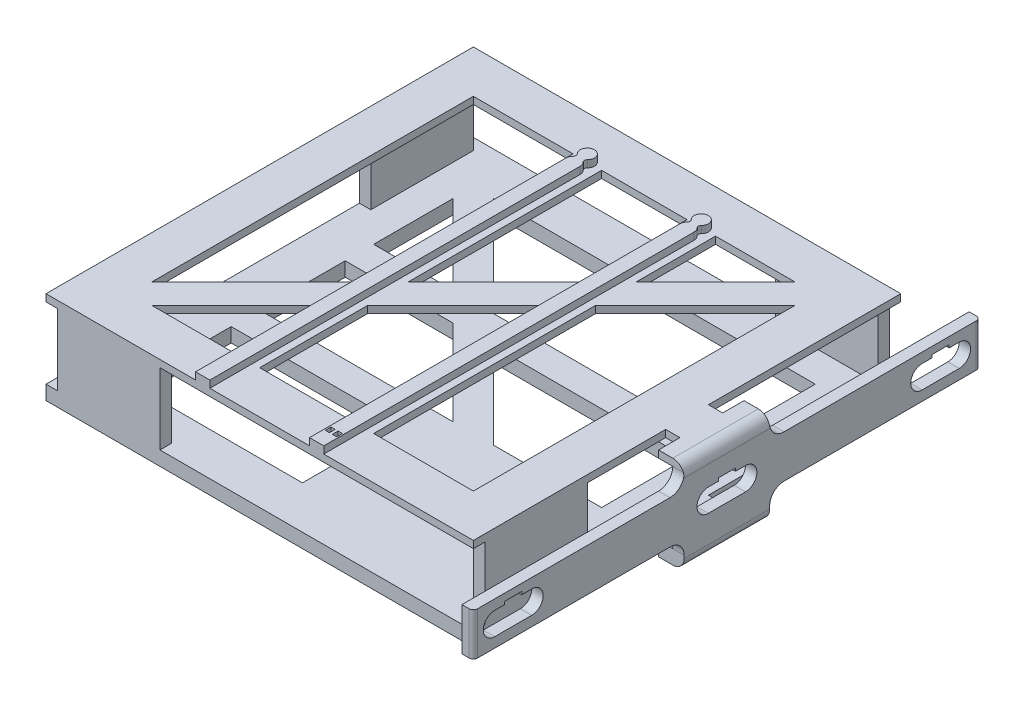
SolidWorks part; units mm, degrees
other "相机1"
material "3.0526 (EN-AW 3005)"
ref_plane "前视基准面" through (0, 0, 0) normal (0, 0, 1) x (1, 0, 0)
ref_plane "上视基准面" through (0, 0, 0) normal (0, 1, 0) x (1, 0, 0)
ref_plane "右视基准面" through (0, 0, 0) normal (1, 0, 0) x (0, 0, -1)
sketch "草图1" plane through (0, 0, 0) normal (0, 1, 0) x (1, 0, 0)
  line L0 (-15.8579, 30) -> (120, 30)
  line L1 (-150, 150) -> (150, 150)
  line L2 (-150, 150) -> (-150, -150)
  line L3 (-150, -150) -> (0, -150)
  line L4 (150, 150) -> (150, -30)
  line L5 (-105.8579, 120) -> (120, 120)
  line L6 (-120, 105.8579) -> (-120, 50)
  line L7 (-120, -120) -> (0, -120)
  line L8 (120, 120) -> (120, 50)
  line L9 (150, -150) -> (0, -150)
  line L10 (150, -150) -> (150, -30)
  line L11 (120, 30) -> (120, -30)
  line L12 (0, -120) -> (0, -50)
  line L13 (-120, 105.8579) -> (-64.1421, 50)
  line L14 (-105.8579, 120) -> (-35.8579, 50)
  line L16 (-120, -50) -> (-120, -120)
  line L17 (-120, 30) -> (-44.1421, 30)
  line L18 (-120, 50) -> (-64.1421, 50)
  line L19 (-120, -50) -> (0, -50)
  line L20 (-120, -30) -> (15.8579, -30)
  line L21 (-120, 30) -> (-120, -30)
  line L22 (44.1421, -30) -> (120, -30)
  line L26 (-44.1421, 30) -> (15.8579, -30)
  line L27 (-15.8579, 30) -> (44.1421, -30)
  line L28 (-35.8579, 50) -> (120, 50)
  point P4 (-120, 120)
  point P5 (120, -120)
  point P11 (-127.0711, 112.9289)
  point P12 (112.9289, -127.0711)
  point P13 (-112.9289, 127.0711)
  point P14 (127.0711, -112.9289)
  point P15 (-120, 40)
  point P16 (120, 40)
  point P17 (-120, -40)
  point P18 (120, -40)
  point P24 (120, -50)
extrude "凸台-拉伸1" add sketch "草图1" along normal blind 5
sketch "草图2" plane through (0, 0, 0) normal (0, -1, 0) x (1, 0, 0)
  line L0 (150, 45) -> (150, 150)
  line L5 (-110, -45) -> (150, -45)
  line L6 (-110, 35) -> (150, 35)
  line L7 (-110, -35) -> (150, -35)
  line L8 (-110, 45) -> (150, 45)
  line L9 (150, 150) -> (-150, 150)
  line L10 (-150, 150) -> (-150, -150)
  line L11 (-150, -150) -> (150, -150)
  line L12 (150, -150) -> (150, -45)
  line L13 (150, -35) -> (150, 35)
  line L14 (-120, 120) -> (-120, 50)
  line L15 (-120, 50) -> (0, 50)
  line L16 (0, 50) -> (0, 120)
  line L17 (0, 120) -> (-120, 120)
  line L18 (-120, 30) -> (-120, -30)
  line L19 (-120, -30) -> (-44.1421, -30)
  line L20 (-44.1421, -30) -> (15.8579, 30)
  line L21 (15.8579, 30) -> (-120, 30)
  line L22 (44.1421, 30) -> (-15.8579, -30)
  line L23 (-15.8579, -30) -> (120, -30)
  line L24 (120, -30) -> (120, 30)
  line L25 (120, 30) -> (44.1421, 30)
  line L26 (-120, -50) -> (-120, -105.8579)
  line L27 (-120, -105.8579) -> (-64.1421, -50)
  line L28 (-64.1421, -50) -> (-120, -50)
  line L29 (-35.8579, -50) -> (-105.8579, -120)
  line L30 (-105.8579, -120) -> (120, -120)
  line L31 (120, -120) -> (120, -50)
  line L32 (120, -50) -> (-35.8579, -50)
  arc A0 (-116.4645, 43.5355) -> (-116.4645, 36.4645) centre (-120, 40) ccw
  arc A1 (-116.4645, 43.5355) -> (-113.5355, 43.5355) centre (-115, 45) ccw
  arc A2 (-113.5355, 36.4645) -> (-116.4645, 36.4645) centre (-115, 35) ccw
  arc A3 (-110, 35) -> (-113.5355, 36.4645) centre (-110, 40) cw
  arc A4 (-113.5355, 43.5355) -> (-110, 45) centre (-110, 40) cw
  arc A5 (-113.5355, -43.5355) -> (-110, -45) centre (-110, -40) ccw
  arc A6 (-116.4645, -43.5355) -> (-113.5355, -43.5355) centre (-115, -45) cw
  arc A7 (-116.4645, -43.5355) -> (-116.4645, -36.4645) centre (-120, -40) cw
  arc A8 (-113.5355, -36.4645) -> (-116.4645, -36.4645) centre (-115, -35) cw
  arc A9 (-110, -35) -> (-113.5355, -36.4645) centre (-110, -40) ccw
  point P5 (-150, 40)
  point P8 (150, 40)
  point P11 (-120, 35)
  point P14 (-120, 45)
extrude "凸台-拉伸2" add sketch "草图2" along normal blind 5
sketch "草图3" plane through (0, 5, 0) normal (0, 1, 0) x (1, 0, 0)
  line L0 (142, -142) -> (150, -142)
  line L1 (-142, -142) -> (-70, -142)
  line L2 (150, -142) -> (150, -70)
  line L3 (150, -70) -> (142, -70)
  line L4 (142, -142) -> (142, -70)
  line L5 (-70, -150) -> (-70, -142)
  line L6 (-142, -142) -> (-142, -150)
  line L7 (-142, -150) -> (-70, -150)
  line L8 (-142, 142) -> (-142, 70)
  line L9 (-150, 70) -> (-142, 70)
  line L10 (-142, 142) -> (-150, 142)
  line L11 (-150, 142) -> (-150, 70)
  line L12 (142, 142) -> (70, 142)
  line L13 (70, 150) -> (70, 142)
  line L14 (142, 142) -> (142, 150)
  line L15 (142, 150) -> (70, 150)
  point P19 (0, 0)
  dimension "D1" = 4
extrude "凸台-拉伸3" add sketch "草图3" along normal blind 50
sketch "草图4" plane through (0, 55, 0) normal (0, 1, 0) x (1, 0, 0)
  line L0 (30, 120) -> (-30, 120)
  line L1 (-150, 150) -> (150, 150)
  line L2 (-150, 150) -> (-150, -150)
  line L3 (-150, -150) -> (150, -150)
  line L4 (150, 150) -> (150, -150)
  line L5 (105.8579, 120) -> (50, 120)
  line L6 (120, 105.8579) -> (120, -120)
  line L7 (120, -120) -> (50, -120)
  line L8 (-120, 120) -> (-120, -105.8579)
  line L9 (105.8579, 120) -> (50, 64.1421)
  line L10 (120, 105.8579) -> (50, 35.8579)
  line L11 (-50, -120) -> (-105.8579, -120)
  line L12 (30, -120) -> (-30, -120)
  line L13 (-50, 120) -> (-50, -35.8579)
  line L14 (-30, 120) -> (-30, -15.8579)
  line L15 (30, 120) -> (30, 44.1421)
  line L16 (50, 120) -> (50, 64.1421)
  line L17 (-50, 120) -> (-120, 120)
  line L18 (-50, -35.8579) -> (-120, -105.8579)
  line L19 (-30, -44.1421) -> (-30, -120)
  line L20 (-50, -64.1421) -> (-105.8579, -120)
  line L22 (-50, -64.1421) -> (-50, -120)
  line L24 (30, 15.8579) -> (30, -120)
  line L25 (30, 44.1421) -> (-30, -15.8579)
  line L27 (50, 35.8579) -> (50, -120)
  line L28 (30, 15.8579) -> (-30, -44.1421)
  point P6 (120, 120)
  point P7 (-120, -120)
  point P12 (112.9289, 127.0711)
  point P13 (-127.0711, -112.9289)
  point P14 (127.0711, 112.9289)
  point P15 (-112.9289, -127.0711)
  point P16 (-40, 120)
  point P17 (-40, -120)
  point P18 (40, 120)
  point P19 (40, -120)
extrude "凸台-拉伸4" add sketch "草图4" along normal blind 5
sketch "草图5" plane through (0, 60, 0) normal (0, 1, 0) x (1, 0, 0)
  line L0 (35, 110) -> (35, -150)
  line L1 (-45, -150) -> (-35, -150)
  line L2 (45, 110) -> (45, -150)
  line L4 (35, -150) -> (45, -150)
  line L5 (-45, 110) -> (-45, -150)
  line L6 (-35, 110) -> (-35, -150)
  arc A0 (-36.4645, 116.4645) -> (-43.5355, 116.4645) centre (-40, 120) ccw
  arc A1 (-36.4645, 116.4645) -> (-36.4645, 113.5355) centre (-35, 115) ccw
  arc A2 (-43.5355, 113.5355) -> (-43.5355, 116.4645) centre (-45, 115) ccw
  arc A3 (43.5355, 116.4645) -> (36.4645, 116.4645) centre (40, 120) ccw
  arc A4 (43.5355, 116.4645) -> (43.5355, 113.5355) centre (45, 115) ccw
  arc A5 (36.4645, 113.5355) -> (36.4645, 116.4645) centre (35, 115) ccw
  arc A6 (-36.4645, 113.5355) -> (-35, 110) centre (-40, 110) cw
  arc A7 (43.5355, 113.5355) -> (45, 110) centre (40, 110) cw
  arc A8 (-45, 110) -> (-43.5355, 113.5355) centre (-40, 110) cw
  arc A9 (35, 110) -> (36.4645, 113.5355) centre (40, 110) cw
  point P9 (-40, -150)
  point P14 (-45, 120)
  point P16 (-35, 120)
  point P18 (35, 120)
  point P20 (45, 120)
extrude "凸台-拉伸5" add sketch "草图5" along normal blind 5
sketch "草图6" plane through (0, 0, 0) normal (0, -1, 0) x (1, 0, 0)
  line L1 (140, 44) -> (136, 44)
  line L2 (140, 44) -> (140, 41)
  line L3 (140, 36) -> (136, 36)
  line L4 (136, 44) -> (136, 41)
  line L7 (136, 39) -> (140, 39)
  line L8 (136, 41) -> (140, 41)
  line L9 (136, 39) -> (136, 36)
  line L10 (140, 39) -> (140, 36)
extrude "切除-拉伸1" cut sketch "草图6" against normal blind 3
sketch "草图7" plane through (0, 3, 0) normal (0, -1, 0) x (1, 0, 0)
  circle A0 centre (138, 43.5) radius 0.4
  circle A1 centre (138, 41.5) radius 0.4
  circle A2 centre (138, 36.5) radius 0.4
  circle A3 centre (138, 38.5) radius 0.4
extrude "切除-拉伸2" cut sketch "草图7" against normal blind 3
sketch "草图8" plane through (0, 65, 0) normal (0, 1, 0) x (1, 0, 0)
  line L0 (39, -136) -> (36, -136)
  line L1 (44, -140) -> (41, -140)
  line L2 (44, -140) -> (44, -136)
  line L3 (44, -136) -> (41, -136)
  line L4 (36, -140) -> (36, -136)
  line L5 (39, -136) -> (39, -140)
  line L6 (41, -136) -> (41, -140)
  line L7 (39, -140) -> (36, -140)
extrude "切除-拉伸3" cut sketch "草图8" against normal blind 3
sketch "草图9" plane through (0, 62, 0) normal (0, 1, 0) x (1, 0, 0)
  circle A0 centre (43.5, -138) radius 0.4
  circle A1 centre (41.5, -138) radius 0.4
  circle A2 centre (36.5, -138) radius 0.4
  circle A3 centre (38.5, -138) radius 0.4
extrude "切除-拉伸4" cut sketch "草图9" against normal blind 3
sketch "草图10" plane through (0, 5, 0) normal (0, 1, 0) x (1, 0, 0)
  line L1 (150, -150) -> (150, 150) construction
  line L2 (150, 15) -> (160, 15)
  line L3 (160, 15) -> (160, 30)
  line L4 (160, 30) -> (178, 30)
  line L5 (178, 30) -> (178, -30)
  line L6 (150, 15) -> (150, -15)
  line L7 (160, -30) -> (178, -30)
  line L8 (160, -15) -> (160, -30)
  line L9 (150, -15) -> (160, -15)
sketch "草图11" plane through (0, 60, 0) normal (0, 1, 0) x (1, 0, 0)
  line L0 (150, 15) -> (160, 15)
  line L1 (160, 15) -> (160, 30)
  line L2 (160, 30) -> (178, 30)
  line L3 (178, 30) -> (178, -30)
  line L4 (178, -30) -> (160, -30)
  line L5 (160, -30) -> (160, -15)
  line L6 (160, -15) -> (150, -15)
  line L7 (150, -15) -> (150, 15)
sketch "草图12" plane through (0, 5, 0) normal (0, 1, 0) x (1, 0, 0)
  line L0 (178, 30) -> (178, 178)
  line L1 (178, 178) -> (170, 178)
  line L2 (170, 178) -> (170, -178)
  line L3 (170, -178) -> (178, -178)
  line L4 (178, -178) -> (178, 30)
extrude "凸台-拉伸6" add sketch "草图11" against normal blind 5
extrude "凸台-拉伸7" add sketch "草图10" against normal blind 10
extrude "凸台-拉伸8" add sketch "草图12" along normal blind 50
sketch "草图13" plane through (178, 0, 0) normal (1, 0, 0) x (0, 0, -1)
  line L0 (40, 15) -> (178, 15)
  line L1 (40, 45) -> (178, 45)
  line L2 (-6, 38) -> (-13, 38)
  line L3 (137, 22) -> (163, 22)
  line L4 (178, 15) -> (178.3425, 14.8245)
  line L5 (-30, 55) -> (-178, 55)
  line L6 (-178, 55) -> (-178, 45)
  line L7 (-178, 15) -> (-40, 15)
  line L8 (-178, 45) -> (-40, 45)
  line L9 (-30, 5) -> (-178, 5)
  line L10 (-178, 5) -> (-178, 15)
  line L11 (30, 55) -> (178, 55)
  line L12 (178, 55) -> (178, 45)
  line L13 (30, 5) -> (178, 5) construction
  line L14 (178, 15) -> (178, 5)
  line L15 (144, 38) -> (137, 38)
  line L16 (178, 5) -> (30, 5)
  line L17 (-6, 40) -> (6, 40)
  line L18 (144, 40) -> (144, 38)
  line L21 (144, 40) -> (156, 40)
  line L22 (-6, 40) -> (-6, 38)
  line L23 (156, 40) -> (156, 38)
  line L24 (13, 38) -> (6, 38)
  line L25 (6, 40) -> (6, 38)
  line L26 (163, 38) -> (156, 38)
  line L27 (-163, 22) -> (-137, 22)
  line L28 (-13, 22) -> (13, 22)
  line L29 (-156, 38) -> (-163, 38)
  line L30 (-156, 40) -> (-156, 38)
  line L31 (-156, 40) -> (-144, 40)
  line L32 (-144, 40) -> (-144, 38)
  line L33 (-137, 38) -> (-144, 38)
  arc A0 (-13, 38) -> (-13, 22) centre (-13, 30) ccw
  arc A1 (13, 38) -> (13, 22) centre (13, 30) cw
  arc A2 (40, 15) -> (30, 5) centre (40, 5) ccw
  arc A3 (-40, 15) -> (-30, 5) centre (-40, 5) cw
  arc A4 (-40, 45) -> (-30, 55) centre (-40, 55) ccw
  arc A5 (40, 45) -> (30, 55) centre (40, 55) cw
  arc A6 (137, 38) -> (137, 22) centre (137, 30) ccw
  arc A7 (163, 38) -> (163, 22) centre (163, 30) cw
  arc A8 (-163, 38) -> (-163, 22) centre (-163, 30) ccw
  arc A9 (-137, 38) -> (-137, 22) centre (-137, 30) cw
  dimension "D1" = 2
  dimension "D2" = 2
extrude "切除-拉伸7" cut sketch "草图13" against normal blind 8 contours L8 A4 L5 L6 | L7 A3 L9 L10 | L1 L12 L11 A5 | L14 L16 A2 L0 | A1 L28 A0 L2 L22 L17 L25 L24 | L3 A7 L26 L23 L21 L18 L15 A6 | L27 A9 L33 L32 L31 L30 L29 A8
fillet "圆角1" radius 8 1 edges at (178, 60, 0)
fillet "圆角2" radius 8 1 edges at (178, -5, 0)
fillet "圆角3" radius 3 2 edges at (178, 30, -178) (178, 30, 178)
